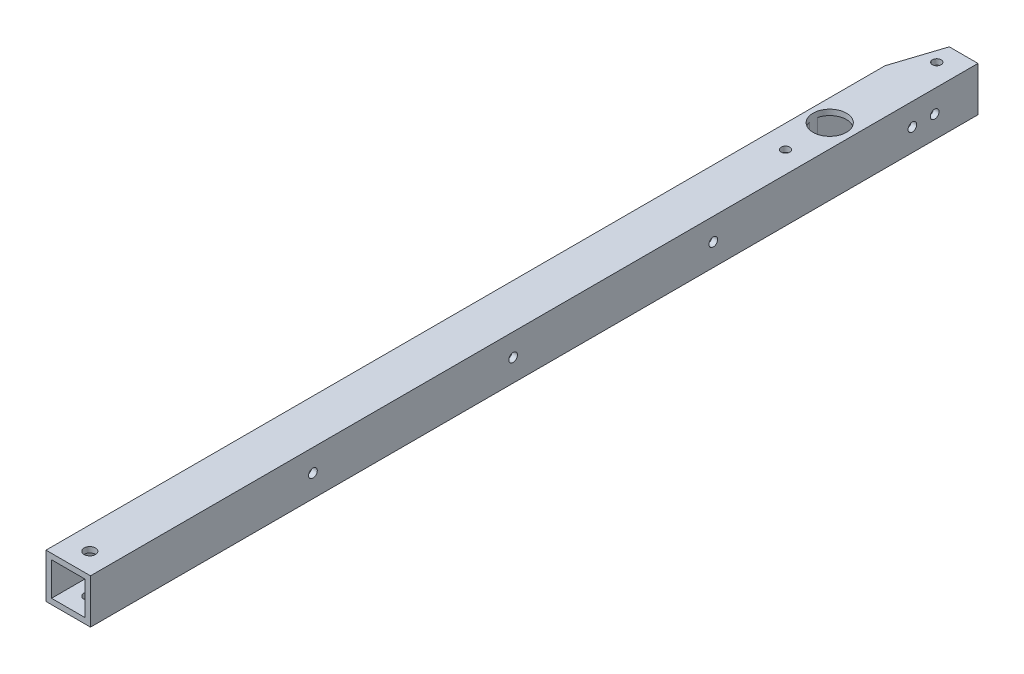
SolidWorks part; units mm, degrees
material "6061 Alloy"
ref_plane "Front Plane" through (0, 0, 0) normal (0, 0, 1) x (1, 0, 0)
ref_plane "Top Plane" through (0, 0, 0) normal (0, 1, 0) x (1, 0, 0)
ref_plane "Right Plane" through (0, 0, 0) normal (1, 0, 0) x (0, 0, -1)
sketch "Sketch1" plane through (0, 0, 0) normal (0, 0, 1) x (1, 0, 0)
  line L0 (-9.525, 9.525) -> (9.525, 9.525)
  line L2 (-12.7, 12.7) -> (12.7, 12.7)
  line L3 (-12.7, 12.7) -> (-12.7, -12.7)
  line L4 (-12.7, -12.7) -> (12.7, -12.7)
  line L5 (12.7, 12.7) -> (12.7, -12.7)
  line L10 (9.525, 9.525) -> (9.525, -9.525)
  line L11 (-9.525, -9.525) -> (9.525, -9.525)
  line L12 (-9.525, 9.525) -> (-9.525, -9.525)
  point P12 (0, 12.7)
  point P14 (12.7, 0)
  dimension "Wall Thickness" = 3.175
  dimension "Outside Width" = 25.4
  dimension "Outside Height" = 25.4
  dimension "Inside Height" = 19.05
  dimension "Inside Width" = 19.05
sketch "Sketch2" plane through (0, 0, 0) normal (1, 0, 0) x (0, 0, -1)
  line L0 (260.35, 0) -> (-260.35, 0)
  point P4 (0, 0)
  point P7 (-260.35, 0)
  point P10 (260.35, 0)
  dimension "Length" = 520.7
sketch "Sketch3" plane through (0, 0, 0) normal (0, 0, 1) x (1, 0, 0)
  line L21 (12.7, 12.7) -> (-12.7, 12.7)
  line L22 (12.7, -12.7) -> (12.7, 12.7)
  line L23 (-12.7, -12.7) -> (12.7, -12.7)
  line L24 (-12.7, 12.7) -> (-12.7, -12.7)
  line L25 (12.7, 12.7) -> (-12.7, 12.7)
  line L26 (12.7, -12.7) -> (12.7, 12.7)
  line L27 (-12.7, -12.7) -> (12.7, -12.7)
  line L28 (-12.7, 12.7) -> (-12.7, -12.7)
  line L29 (9.525, 9.525) -> (-9.525, 9.525)
  line L30 (9.525, -9.525) -> (9.525, 9.525)
  line L31 (-9.525, -9.525) -> (9.525, -9.525)
  line L32 (-9.525, 9.525) -> (-9.525, -9.525)
  line L33 (9.525, 9.525) -> (-9.525, 9.525)
  line L34 (9.525, -9.525) -> (9.525, 9.525)
  line L35 (-9.525, -9.525) -> (9.525, -9.525)
  line L36 (-9.525, 9.525) -> (-9.525, -9.525)
  dimension "D1" = 0
  dimension "D2" = 0
extrude "Boss-Extrude1" add sketch "Sketch3" along normal up to vertex (260.35 mm away) and the other way up to vertex (260.35 mm away) up to point (0, 0, 260.35) other way up to point (0, 0, -260.35)
sketch "Drawing Reference" plane through (0, 0, 0) normal (1, 0, 0) x (0, 0, -1)
  line L0 (-260.35, 0) -> (260.35, 0) construction
  line L1 (0, -12.7) -> (0, 12.7) construction
  line L2 (-260.35, -12.7) -> (260.35, -12.7) construction
  line L5 (-260.35, 12.7) -> (260.35, 12.7) construction
  point P7 (-242.062, 0)
  point P8 (242.062, 0)
  dimension "D1" = 18.288
sketch "Sketch4" plane through (0, 12.7, 0) normal (0, 1, 0) x (1, 0, 0)
  line L7 (-12.7, 218.6635) -> (-12.7, 260.35)
  line L10 (-12.7, -260.35) -> (-12.7, 260.35) construction
  line L11 (-12.7, 260.35) -> (12.7, 260.35)
  line L12 (12.7, 260.35) -> (12.7, 246.38)
  line L13 (12.7, -260.35) -> (12.7, 260.35) construction
  line L14 (12.7, 246.38) -> (-3.6932, 246.38)
  line L15 (-3.6932, 246.38) -> (-12.7, 218.6635)
  dimension "D1" = 13.97
  dimension "D2" = 41.6865
  dimension "D3" = 9.0068
extrude "Cut-Extrude1" cut sketch "Sketch4" against normal blind 25.4
sketch "Sketch5" plane through (0, -12.7, 0) normal (0, -1, 0) x (1, 0, 0)
  circle A0 centre (-0.278, -174.7033) radius 9.525
extrude "Cut-Extrude2" cut sketch "Sketch5" against normal through all
sketch "Sketch6" plane through (12.7, 0, 0) normal (1, 0, 0) x (0, 0, -1)
  line L0 (246.38, 0) -> (208.915, 0) construction
  line L1 (246.38, -12.7) -> (246.38, 12.7) construction
  line L2 (208.915, 0) -> (221.615, 0) construction
  dimension "D1" = 37.465
hole_wizard "#10 Clearance Hole2" positions "Sketch9" profile "Sketch10" hole size "#10" standard "ANSI Inch" end condition through all
sketch "Sketch9" plane through (0, 12.7, 0) normal (0, 1, 0) x (1, 0, 0)
  point P0 (0.3797, 148.7865)
  point P3 (0.3831, 235.1731)
sketch "Sketch10" plane through (0.3797, 12.7, -148.7865) normal (1, 0, 0) x (0, 0, 1)
  line L0 (0, 0) -> (0, 25.4)
  line L1 (0, 25.4) -> (2.4892, 25.4)
  line L2 (2.4892, 25.4) -> (2.4892, 0)
  line L5 (2.4892, 0) -> (0, 0)
  line L11 (0, -6.35) -> (0, 107.95) construction
  dimension "Thru Hole Dia." = 4.9784
  dimension "Thru Hole Depth" = 25.4
sketch "Sketch20" plane through (0, 12.7, 0) normal (0, 1, 0) x (1, 0, 0)
  line L0 (0.364, -248.3815) -> (0.364, -260.35) construction
  line L1 (12.7, -260.35) -> (-12.7, -260.35) construction
  circle A0 centre (0.364, -248.3815) radius 3.175 construction
  point P2 (0, -260.35)
  dimension "D1" = 11.9685
  dimension "D2" = 0.364
hole_wizard "1/4 Clearance Hole2" positions "Sketch13" profile "Sketch14" hole size "1/4" standard "ANSI Inch" end condition through all
sketch "Sketch13" plane through (0, 12.7, 0) normal (0, 1, 0) x (1, 0, 0)
  point P0 (0.364, -248.3815)
sketch "Sketch14" plane through (0.364, 12.7, 248.3815) normal (1, 0, 0) x (0, 0, 1)
  line L0 (0, 0) -> (0, 25.4)
  line L1 (0, 25.4) -> (3.2639, 25.4)
  line L2 (3.2639, 25.4) -> (3.2639, 0)
  line L5 (3.2639, 0) -> (0, 0)
  line L11 (0, -6.35) -> (0, 107.95) construction
  dimension "Thru Hole Dia." = 6.5278
  dimension "Thru Hole Depth" = 25.4
hole_wizard "#10 Clearance Hole3" positions "Sketch15" profile "Sketch16" hole size "#10" standard "ANSI Inch"
sketch "Sketch15" plane through (12.7, 0, 0) normal (1, 0, 0) x (0, 0, -1)
  point P0 (221.615, 0)
  point P4 (208.915, 0)
sketch "Sketch16" plane through (12.7, 0, -221.615) normal (0, 1, 0) x (0, 0, -1)
  line L0 (0, 0) -> (0, 6.5757)
  line L1 (0, 6.5757) -> (2.4892, 5.08)
  line L2 (2.4892, 5.08) -> (2.4892, 0)
  line L5 (2.4892, 0) -> (0, 0)
  line L10 (0, 6.5757) -> (-2.4892, 5.08) construction
  line L11 (0, -6.35) -> (0, 107.95) construction
  dimension "Hole Dia." = 4.9784
  dimension "Hole Depth" = 5.08
  dimension "Drill Angle" = 118
sketch "Sketch17" plane through (12.7, 0, 0) normal (1, 0, 0) x (0, 0, -1)
  line L0 (-260.35, 0) -> (-133.35, 0) construction
  line L1 (-260.35, -12.7) -> (-260.35, 12.7) construction
  line L2 (-133.35, 0) -> (-19.05, 0) construction
  line L3 (-19.05, 0) -> (95.25, 0) construction
  dimension "D1" = 127
  dimension "D2" = 114.3
  dimension "D3" = 114.3
hole_wizard "#10 Clearance Hole4" positions "Sketch18" profile "Sketch19" hole size "#10" standard "ANSI Inch" end condition through all
sketch "Sketch18" plane through (12.7, 0, 0) normal (1, 0, 0) x (0, 0, -1)
  point P0 (-133.35, 0)
  point P3 (-19.05, 0)
  point P6 (95.25, 0)
sketch "Sketch19" plane through (12.7, 0, 133.35) normal (0, 1, 0) x (0, 0, -1)
  line L0 (0, 0) -> (0, 25.4)
  line L1 (0, 25.4) -> (2.4892, 25.4)
  line L2 (2.4892, 25.4) -> (2.4892, 0)
  line L5 (2.4892, 0) -> (0, 0)
  line L11 (0, -6.35) -> (0, 107.95) construction
  dimension "Thru Hole Dia." = 4.9784
  dimension "Thru Hole Depth" = 25.4
equation "\"D1@Drawing Reference\"=\"Outside Width@Sketch1\" * 0.72"
